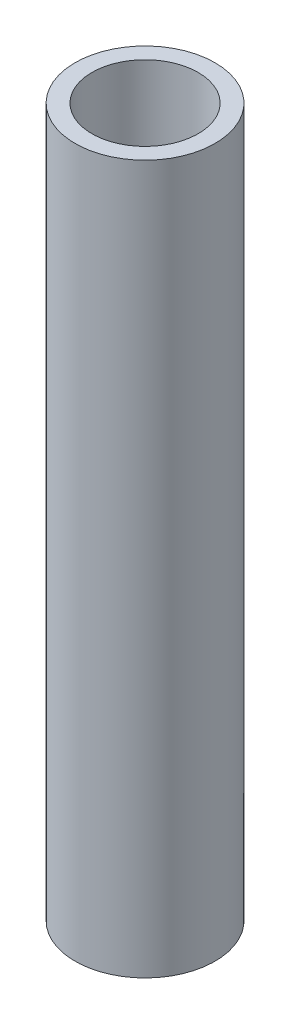
SolidWorks part; units mm, degrees
ref_plane "Front Plane" through (0, 0, 0) normal (0, 0, 1) x (1, 0, 0)
ref_plane "Top Plane" through (0, 0, 0) normal (0, 1, 0) x (1, 0, 0)
ref_plane "Right Plane" through (0, 0, 0) normal (1, 0, 0) x (0, 0, -1)
sketch "Sketch1" plane through (0, 0, 0) normal (0, 1, 0) x (1, 0, 0)
  circle A0 centre (0, 0) radius 3.15
  circle A1 centre (0, 0) radius 4.15
  dimension "D1" = 6.3
  dimension "D2" = 1
extrude "Boss-Extrude1" add sketch "Sketch1" along normal blind 42
